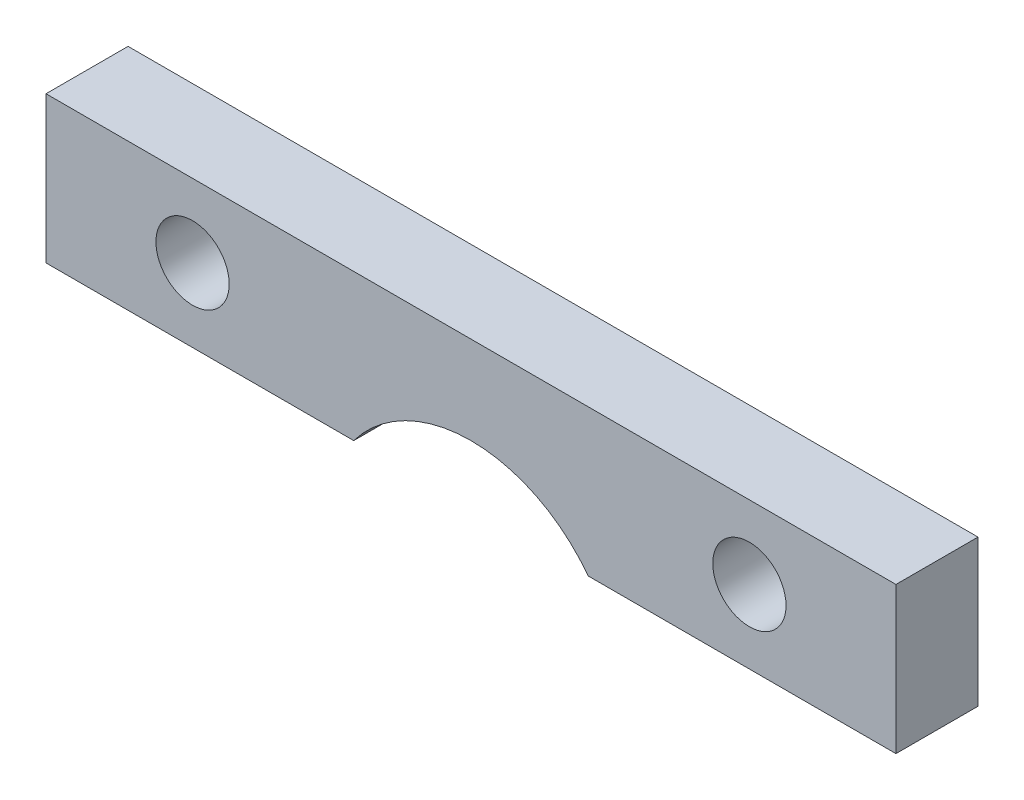
SolidWorks part; units mm, degrees
ref_plane "Front Plane" through (0, 0, 0) normal (0, 0, 1) x (1, 0, 0)
ref_plane "Top Plane" through (0, 0, 0) normal (0, 1, 0) x (1, 0, 0)
ref_plane "Right Plane" through (0, 0, 0) normal (1, 0, 0) x (0, 0, -1)
sketch "Sketch1" plane through (0, 0, 0) normal (0, 0, 1) x (1, 0, 0)
  line L0 (46.99, 0) -> (73.66, 0)
  line L1 (0, 0) -> (26.67, 0)
  line L2 (0, 0) -> (0, 12.7)
  line L3 (0, 12.7) -> (73.66, 12.7)
  line L4 (73.66, 0) -> (73.66, 12.7)
  circle A0 centre (12.7, 6.35) radius 3.175
  circle A1 centre (60.96, 6.35) radius 3.175
  arc A2 (46.99, 0) -> (26.67, 0) centre (36.83, -7.62) ccw
  point P9 (0, 0)
  point P10 (27.7173, 0)
  point P11 (0, 6.35)
  point P13 (0, 0)
  point P16 (0, 0)
  point P17 (36.83, 12.7)
  dimension "D1" = 6.35
  dimension "D6" = 25.4
  dimension "D2" = 48.26
  dimension "D3" = 73.66
  dimension "D4" = 12.7
  dimension "D5" = 12.7
  dimension "D7" = 7.62
extrude "Boss-Extrude1" add sketch "Sketch1" along normal blind 7.112
